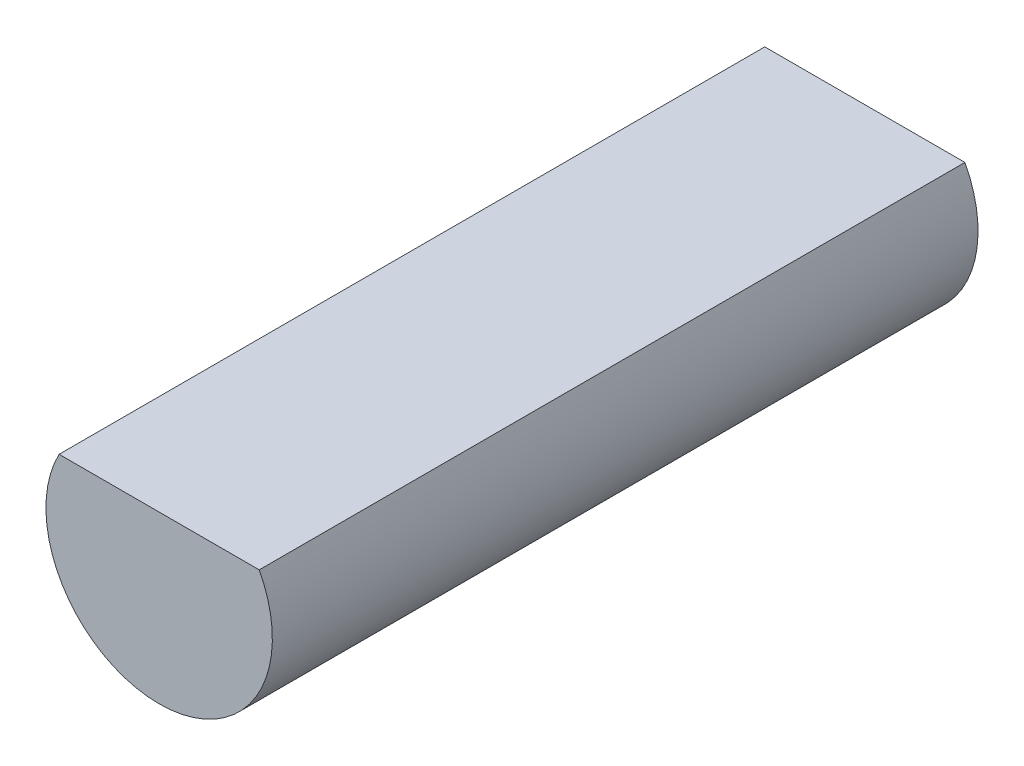
SolidWorks part; units mm, degrees
ref_plane "Front Plane" through (0, 0, 0) normal (0, 0, 1) x (1, 0, 0)
ref_plane "Top Plane" through (0, 0, 0) normal (0, 1, 0) x (1, 0, 0)
ref_plane "Right Plane" through (0, 0, 0) normal (1, 0, 0) x (0, 0, -1)
sketch "Sketch1" plane through (0, 0, 0) normal (0, 0, 1) x (1, 0, 0)
  line L0 (-1.7017, 0.9) -> (1.7017, 0.9)
  circle A0 centre (0, 0) radius 1.925
  dimension "D1" = 3.85
  dimension "D2" = 0.9
extrude "Boss-Extrude1" add sketch "Sketch1" along normal blind 12 contours L0 A0
